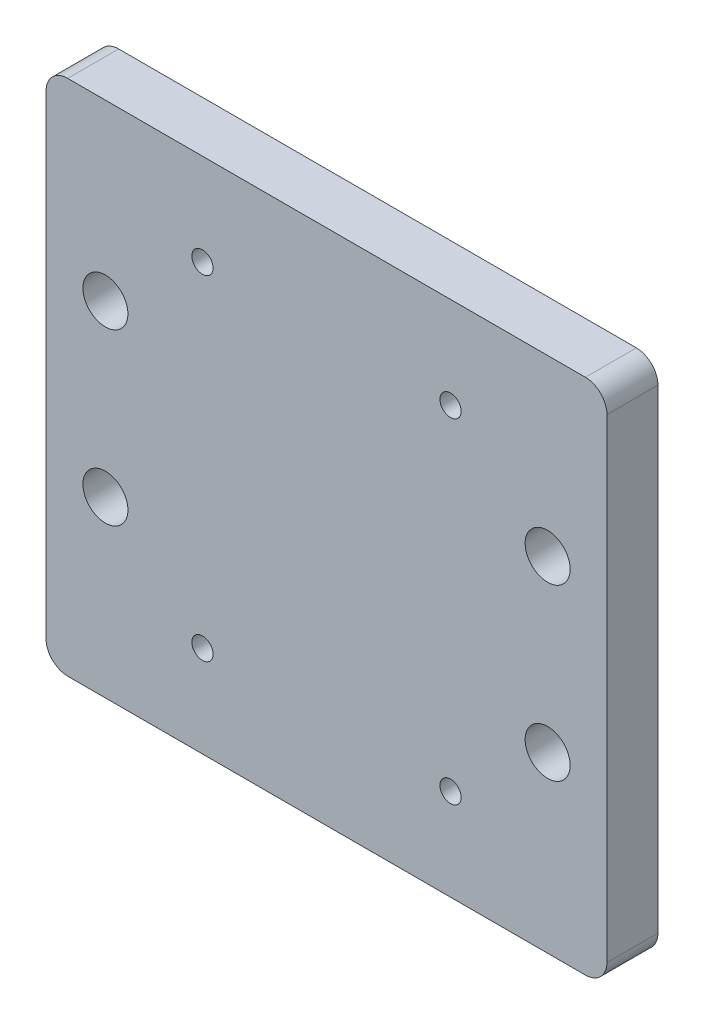
SolidWorks part; units mm, degrees
ref_plane "Front Plane" through (0, 0, 0) normal (0, 0, 1) x (1, 0, 0)
ref_plane "Top Plane" through (0, 0, 0) normal (0, 1, 0) x (1, 0, 0)
ref_plane "Right Plane" through (0, 0, 0) normal (1, 0, 0) x (0, 0, -1)
other "Configuration Table"
ref_plane "Plane1" through (0, 0, -12) normal (0, 0, -1) x (-1, 0, 0)
sketch "Sketch1" plane through (0, 0, -12) normal (0, 0, -1) x (-1, 0, 0)
  line L0 (-528.6121, 403.6314) -> (-462.5721, 403.6314) construction
  line L1 (-526.0721, 434.1114) -> (-465.1121, 434.1114)
  line L2 (-528.6121, 431.5714) -> (-528.6121, 375.6914)
  line L3 (-526.0721, 373.1514) -> (-465.1121, 373.1514)
  line L4 (-495.5921, 413.6314) -> (-495.5921, 403.6314) construction
  line L5 (-495.5921, 403.6314) -> (-495.5921, 393.6314) construction
  line L6 (-515.6271, 413.6314) -> (-514.6421, 413.6314) construction
  line L7 (-528.6121, 413.6314) -> (-527.6271, 413.6314) construction
  line L20 (-462.5721, 431.5714) -> (-462.5721, 375.6914)
  line L21 (-528.6121, 413.6314) -> (-462.5721, 413.6314) construction
  line L22 (-462.5721, 393.6314) -> (-528.6121, 393.6314) construction
  line L23 (-476.5421, 382.0414) -> (-476.5421, 425.2214)
  line L24 (-479.0821, 427.7614) -> (-512.1021, 427.7614)
  line L25 (-528.6121, 413.6314) -> (-521.6271, 413.6314) construction
  line L26 (-521.6271, 413.6314) -> (-528.6121, 413.6314) construction
  line L27 (-514.6421, 425.2214) -> (-514.6421, 382.0414)
  line L28 (-512.1021, 379.5014) -> (-479.0821, 379.5014)
  line L29 (-476.5421, 382.0414) -> (-476.5421, 425.2214) construction
  line L30 (-479.0821, 427.7614) -> (-512.1021, 427.7614) construction
  line L31 (-514.6421, 425.2214) -> (-514.6421, 382.0414) construction
  line L32 (-512.1021, 379.5014) -> (-479.0821, 379.5014) construction
  line L33 (-475.5571, 413.6314) -> (-476.5421, 413.6314) construction
  line L34 (-463.5571, 413.6314) -> (-462.5721, 413.6314) construction
  circle A1 centre (-480.9871, 383.9464) radius 1.575
  circle A2 centre (-480.9871, 383.9464) radius 1.575 construction
  circle A3 centre (-480.9871, 423.3164) radius 1.575
  circle A4 centre (-480.9871, 423.3164) radius 1.575 construction
  circle A5 centre (-510.1971, 423.3164) radius 1.575
  circle A6 centre (-510.1971, 423.3164) radius 1.575 construction
  circle A7 centre (-510.1971, 383.9464) radius 1.575
  circle A20 centre (-510.1971, 383.9464) radius 1.575 construction
  circle A26 centre (-521.6271, 413.6314) radius 6 construction
  circle A27 centre (-521.6271, 393.6314) radius 6 construction
  circle A28 centre (-469.5571, 393.6314) radius 6 construction
  circle A29 centre (-469.5571, 413.6314) radius 6 construction
  arc A30 (-465.1121, 434.1114) -> (-462.5721, 431.5714) centre (-465.1121, 431.5714) cw
  arc A31 (-465.1121, 373.1514) -> (-462.5721, 375.6914) centre (-465.1121, 375.6914) ccw
  arc A32 (-528.6121, 375.6914) -> (-526.0721, 373.1514) centre (-526.0721, 375.6914) ccw
  arc A33 (-526.0721, 434.1114) -> (-528.6121, 431.5714) centre (-526.0721, 431.5714) ccw
  circle A34 centre (-497.0201, 406.0314) radius 0.725
  circle A35 centre (-497.0201, 406.0314) radius 0.725 construction
  circle A36 centre (-505.2201, 406.0314) radius 0.725
  circle A37 centre (-505.2201, 406.0314) radius 0.725 construction
  circle A38 centre (-505.2201, 401.0314) radius 0.725
  circle A39 centre (-505.2201, 401.0314) radius 0.725 construction
  circle A40 centre (-497.0201, 401.0314) radius 0.725
  circle A41 centre (-497.0201, 401.0314) radius 0.725 construction
  arc A45 (-479.0821, 379.5014) -> (-476.5421, 382.0414) centre (-479.0821, 382.0414) ccw
  arc A46 (-476.5421, 425.2214) -> (-479.0821, 427.7614) centre (-479.0821, 425.2214) ccw
  arc A47 (-512.1021, 427.7614) -> (-514.6421, 425.2214) centre (-512.1021, 425.2214) ccw
  arc A48 (-514.6421, 382.0414) -> (-512.1021, 379.5014) centre (-512.1021, 382.0414) ccw
  arc A49 (-479.0821, 379.5014) -> (-476.5421, 382.0414) centre (-479.0821, 382.0414) ccw construction
  arc A50 (-476.5421, 425.2214) -> (-479.0821, 427.7614) centre (-479.0821, 425.2214) ccw construction
  arc A51 (-512.1021, 427.7614) -> (-514.6421, 425.2214) centre (-512.1021, 425.2214) ccw construction
  arc A52 (-514.6421, 382.0414) -> (-512.1021, 379.5014) centre (-512.1021, 382.0414) ccw construction
  dimension "D3" = 12
  dimension "D8" = 2.54
  dimension "D12" = 6.35
  dimension "D13" = 6.35
  dimension "D14" = 20
  dimension "D15" = 13.97
  dimension "D1" = 0
  dimension "D4" = 0
  dimension "D5" = 0
  dimension "D6" = 0
  dimension "D7" = 0
  dimension "D9" = 0
  dimension "D10" = 0
  dimension "D11" = 0
extrude "Boss-Extrude1" add sketch "Sketch1" along normal blind 6
hole_wizard "M5 Clearance Hole1" positions "Sketch3" profile "Sketch4" hole size "M5" standard "ANSI Metric" end condition through all
sketch "Sketch3" plane through (0, 0, -18) normal (0, 0, -1) x (-1, 0, 0)
  point P0 (-521.6271, 413.6314)
  point P3 (-521.6271, 393.6314)
  point P6 (-469.5571, 393.6314)
  point P9 (-469.5571, 413.6314)
sketch "Sketch4" plane through (521.6271, 413.6314, -18) normal (1, 0, 0) x (0, 1, 0)
  line L0 (0, 0) -> (0, 6)
  line L1 (0, 6) -> (2.65, 6)
  line L2 (2.65, 6) -> (2.65, 0)
  line L5 (2.65, 0) -> (0, 0)
  line L11 (0, -6.35) -> (0, 107.95) construction
  dimension "Thru Hole Dia." = 5.3
  dimension "Thru Hole Depth" = 6
hole_wizard "M3x0.5 Tapped Hole1" positions "Sketch5" profile "Sketch6" tap size "M3x0.5" standard "ANSI Metric" end condition through all
sketch "Sketch5" plane through (0, 0, -18) normal (0, 0, -1) x (-1, 0, 0)
  point P15 (-510.1971, 423.3164)
  point P18 (-480.9871, 423.3164)
  point P21 (-480.9871, 383.9464)
  point P24 (-510.1971, 383.9464)
sketch "Sketch6" plane through (510.1971, 423.3164, -18) normal (1, 0, 0) x (0, 1, 0)
  line L0 (0, 0) -> (0, 6)
  line L1 (0, 6) -> (1.25, 6)
  line L2 (1.25, 6) -> (1.25, 0)
  line L5 (1.25, 0) -> (0, 0)
  line L11 (0, -6.35) -> (0, 107.95) construction
  dimension "Thru Tap Drill Dia." = 2.5
  dimension "Thru Tap Drill Depth" = 6
cosmetic thread "Hole Thread5" parameters "D2"=3
cosmetic thread "Hole Thread6" parameters "D2"=3
cosmetic thread "Hole Thread7" parameters "D2"=3
cosmetic thread "Hole Thread8" parameters "D2"=3
equation "\"D14@Sketch1\"=20mm"
